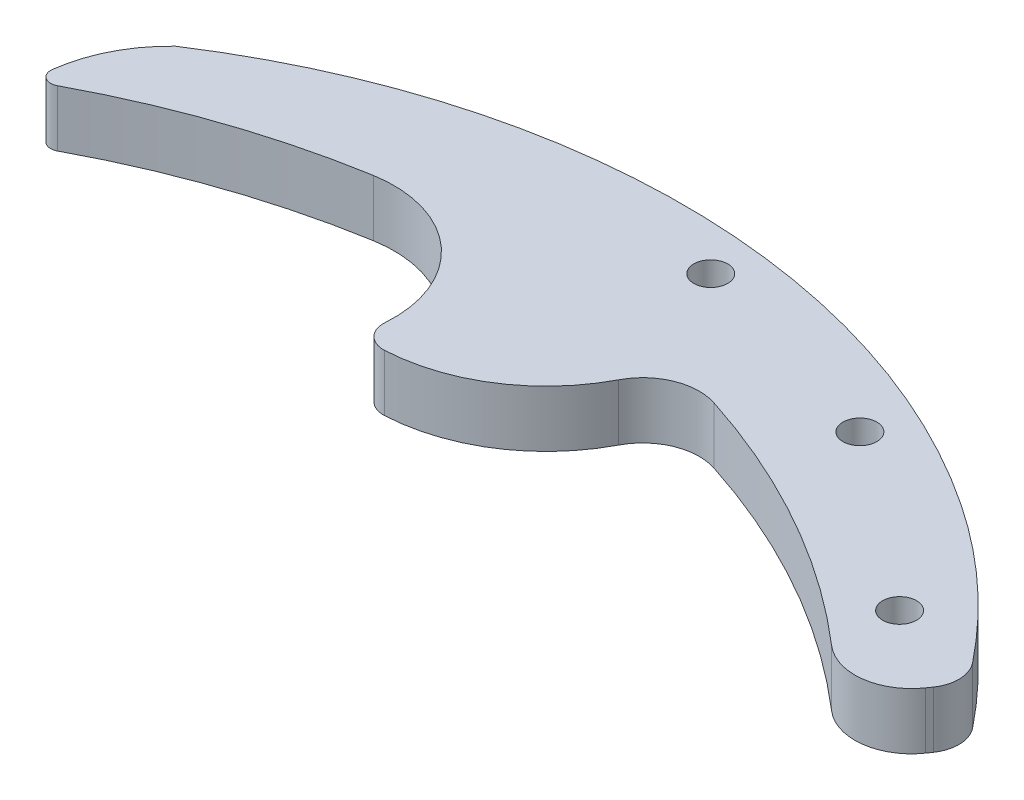
SolidWorks part; units mm, degrees
ref_plane "前视基准面" through (0, 0, 0) normal (0, 0, 1) x (1, 0, 0)
ref_plane "上视基准面" through (0, 0, 0) normal (0, 1, 0) x (1, 0, 0)
ref_plane "右视基准面" through (0, 0, 0) normal (1, 0, 0) x (0, 0, -1)
sketch "草图1" plane through (0, 0, 0) normal (0, 1, 0) x (1, 0, 0)
  line L0 (1.5548, -8.3375) -> (-0.4302, -6.7213)
  line L1 (8.1432, -4.501) -> (5.9156, -7.7187)
  circle A0 centre (-81.4137, 0.5413) radius 1.5
  circle A1 centre (0.783, -0.1362) radius 1.5
  circle A2 centre (-33.3548, 17.3022) radius 1.5
  arc A3 (1.5548, -8.3375) -> (5.9156, -7.7187) centre (3.449, -6.0111) ccw
  arc A4 (8.0213, -0.9218) -> (-4.5749, 10.6629) centre (-35.7028, -35.823) ccw
  arc A5 (8.1432, -4.501) -> (8.0213, -0.9218) centre (5.6767, -2.7934) ccw
  spline S0 degree 3 poles (-12.167, 2.5825) (-11.4471, 1.9213) (-10.023, 2.8082) (-8.9764, 1.8091) (-8.2135, 1.404) (-8.2004, 0.3499) (-8.0426, -0.494) (-7.819, -1.4294) (-6.8169, -1.7535) (-5.8636, -1.3425) (-4.7413, -1.711) (-4.0828, -2.6214) (-3.7925, -3.7512) (-3.9105, -4.8693) (-3.2321, -5.6268) (-2.2067, -6.0304) (-1.0461, -6.0626) (-0.5549, -6.5645) (-0.4302, -6.7213) knots 0 0 0 0 0.036098 0.047993 0.058182 0.069735 0.087709 0.096698 0.107024 0.126401 0.138603 0.153227 0.171393 0.187122 0.197486 0.211172 0.233173 0.241578 0.241578 0.241578 0.241578
  spline S1 degree 3 poles (-23.9106, 9.6057) (-23.5583, 9.383) (-22.85, 7.3001) (-21.4691, 8.0266) (-20.5876, 8.1152) (-19.7095, 8.3931) (-18.8874, 8.017) (-18.2164, 7.2706) (-17.5409, 6.4954) (-16.9173, 5.1698) (-15.3663, 5.5887) (-13.9067, 5.7479) (-12.701, 4.3501) (-12.8698, 3.1094) (-12.167, 2.5825) knots 0 0 0 0 0.161236 0.212348 0.265446 0.336193 0.378688 0.430637 0.526782 0.58317 0.682557 0.781271 0.853714 1 1 1 1
  spline S2 degree 3 poles (-47.715, 10.6051) (-47.069, 9.9007) (-45.1392, 9.958) (-43.922, 11.5864) (-42.4007, 11.771) (-41.3375, 11.3077) (-40.4081, 10.5714) (-39.2433, 10.6059) (-38.4214, 11.3898) (-37.3041, 11.739) (-35.96, 12.1777) (-35.1697, 11.0959) (-34.3091, 10.5976) (-33.2302, 10.3268) (-32.4836, 11.1725) (-31.5559, 11.5569) (-30.4962, 11.8332) (-29.5446, 11.0114) (-28.7649, 9.931) (-27.275, 9.7916) (-25.6779, 9.9955) (-24.4296, 10.4937) (-23.9106, 9.6057) knots 0 0 0 0 0.101433 0.182304 0.213922 0.268057 0.309966 0.345938 0.38914 0.432999 0.482664 0.529097 0.56672 0.598853 0.644173 0.680167 0.715861 0.759457 0.810996 0.863338 0.916048 1 1 1 1
  spline S3 degree 3 poles (-81.5422, -6.3513) (-81.0448, -4.2136) (-76.4233, -7.0442) (-77.1939, -1.4346) (-74.4996, -1.0071) (-72.1196, -0.982) (-72.0139, 2.5319) (-69.1934, 2.2708) (-66.979, 2.5768) (-66.7933, 4.5615) (-65.2282, 5.8665) (-63.7043, 5.4312) (-62.4807, 5.2334) (-61.4837, 6.1991) (-61.3006, 7.5032) (-59.7831, 8.3976) (-58.5198, 7.7031) (-57.096, 7.6588) (-55.836, 8.2946) (-55.3246, 9.9013) (-53.5853, 9.7021) (-52.4002, 9.4229) (-50.5844, 8.8131) (-50.168, 11.1139) (-48.3352, 11.1661) (-47.715, 10.6051) knots 0 0 0 0 0.100332 0.18604 0.234954 0.2703 0.337742 0.40192 0.43828 0.47683 0.523229 0.559517 0.584173 0.604077 0.648703 0.670042 0.71595 0.738313 0.768611 0.808998 0.834826 0.875875 0.9064 0.941714 1 1 1 1
  spline S4 degree 3 poles (-4.5749, 10.6629) (-7.0478, 12.3188) (-11.4724, 14.6182) (-18.6446, 18.4463) (-25.5528, 20.2853) (-32.3111, 21.7651) (-38.4562, 22.3345) (-46.0367, 22.338) (-53.5806, 21.3214) (-60.3919, 19.2596) (-67.9165, 16.4006) (-77.0441, 11.4902) (-84.2299, 5.0961) (-88.4718, 0.1048) (-88.5463, -3.0993) (-86.896, -6.5347) (-83.4963, -7.4095) (-81.5422, -6.3513) knots 0.083499 0.083499 0.083499 0.083499 0.162309 0.214041 0.297346 0.349154 0.396315 0.45953 0.548645 0.595484 0.646703 0.76082 0.864659 0.902713 0.926128 0.944547 1 1 1 1
extrude "凸台-拉伸1" add sketch "草图1" along normal blind 1.2
sketch "草图2" plane through (0, 1.2, 0) normal (0, 1, 0) x (1, 0, 0)
  line L0 (8.1432, -4.501) -> (5.9156, -7.7187)
  arc A0 (-4.5749, 10.6629) -> (8.0213, -0.9218) centre (-35.7028, -35.823) cw
  arc A1 (8.0213, -0.9218) -> (8.1432, -4.501) centre (5.6767, -2.7934) cw
  arc A2 (5.9156, -7.7187) -> (1.5548, -8.3375) centre (3.449, -6.0111) cw
  arc A3 (1.5548, -8.3375) -> (-81.5422, -6.3513) centre (-41.2747, -60.9404) ccw
  arc A4 (-4.5749, 10.6629) -> (-88.4233, -1.3571) centre (-39.8161, -41.9658) ccw
  arc A5 (-88.4233, -1.3571) -> (-81.5422, -6.3513) centre (-84.1899, -2.7618) ccw
  spline S1 degree 3 poles (-4.5749, 10.6629) (-7.0478, 12.3188) (-11.4724, 14.6182) (-18.6446, 18.4463) (-25.5528, 20.2853) (-32.3111, 21.7651) (-38.4562, 22.3345) (-46.0367, 22.338) (-53.5806, 21.3214) (-60.3919, 19.2596) (-67.9165, 16.4006) (-77.0441, 11.4902) (-84.2299, 5.0961) (-88.4718, 0.1048) (-88.5463, -3.0993) (-86.896, -6.5347) (-83.4963, -7.4095) (-81.5422, -6.3513) knots 0.083499 0.083499 0.083499 0.083499 0.162309 0.214041 0.297346 0.349154 0.396315 0.45953 0.548645 0.595484 0.646703 0.76082 0.864659 0.902713 0.926128 0.944547 1 1 1 1 construction
extrude "凸台-拉伸2" add sketch "草图2" along normal blind 10
sketch "草图3" plane through (0, 11.2, 0) normal (0, 1, 0) x (1, 0, 0)
  line L1 (-87.507, -5.7437) -> (-106.1413, 14.9858)
  line L2 (-106.1413, 14.9858) -> (-8.2419, 31.2068)
  line L3 (-8.2419, 31.2068) -> (8.9622, 13.4293)
  line L4 (8.9622, 13.4293) -> (8.0213, -0.9218)
  line L5 (1.5548, -8.3375) -> (-81.5422, -6.3513)
  arc A0 (-88.4233, -1.3571) -> (-4.5749, 10.6629) centre (-39.8161, -41.9658) cw
  arc A1 (-4.5749, 10.6629) -> (2.1688, 5.355) centre (-35.7028, -35.823) cw
  arc A2 (8.0213, -0.9218) -> (-4.5749, 10.6629) centre (-35.7028, -35.823) ccw construction
  arc A3 (2.1688, 5.355) -> (8.0213, -0.9218) centre (-35.7028, -35.823) cw
  arc A6 (1.5548, -8.3375) -> (-81.5422, -6.3513) centre (-41.2747, -60.9404) ccw
  arc A7 (-88.4233, -1.3571) -> (-87.507, -5.7437) centre (-84.1899, -2.7618) ccw
extrude "切除-拉伸1" cut sketch "草图3" against normal through all both and the other way through all
sketch "草图4" plane through (0, 0, 0) normal (0, -1, 0) x (1, 0, 0)
  circle A0 centre (0.783, 0.1362) radius 1.5
extrude "切除-拉伸2" cut sketch "草图4" against normal blind 5000
sketch "草图5" plane through (0, 0, 0) normal (0, -1, 0) x (-1, 0, 0)
  circle A0 centre (33.3548, 17.3022) radius 1.5
  circle A1 centre (81.4137, 0.5413) radius 1.5
extrude "切除-拉伸3" cut sketch "草图5" against normal blind 500
sketch "草图9" plane through (0, 0, 0) normal (0, -1, 0) x (1, 0, 0)
  arc A0 (-33.3548, -17.3022) -> (0.783, 0.1362) centre (-38.7124, 35.3197) ccw construction
  arc A3 (-4.5749, -10.6629) -> (8.0213, 0.9218) centre (-35.7028, 35.823) ccw construction
  circle A4 centre (-14.6505, -11.7844) radius 1.5
  dimension "D1" = 3
extrude "切除-拉伸6" cut sketch "草图9" against normal blind 500
sketch "草图6" plane through (0, 0, 0) normal (0, -1, 0) x (1, 0, 0)
  line L1 (-111.3678, 10.4513) -> (22.6991, 10.4513)
  line L2 (-111.3678, 10.4513) -> (-111.3678, -37.8774)
  line L3 (-111.3678, -37.8774) -> (22.6991, -37.8774)
  line L4 (22.6991, 10.4513) -> (22.6991, -37.8774)
  line L5 (-111.3678, 10.4513) -> (22.6991, -37.8774) construction
  line L6 (-111.3678, -37.8774) -> (22.6991, 10.4513) construction
  point P0 (-44.3344, -13.7131)
extrude "切除-拉伸4" cut sketch "草图6" against normal up to surface (1.2 mm away)
sketch "草图7" plane through (0, 1.2, 0) normal (0, -1, 0) x (1, 0, 0)
  line L1 (-115.2098, 16.5177) -> (21.0814, 16.5177)
  line L2 (-115.2098, 16.5177) -> (-115.2098, -38.0797)
  line L3 (-115.2098, -38.0797) -> (21.0814, -38.0797)
  line L4 (21.0814, 16.5177) -> (21.0814, -38.0797)
  line L5 (-115.2098, 16.5177) -> (21.0814, -38.0797) construction
  line L6 (-115.2098, -38.0797) -> (21.0814, 16.5177) construction
  point P0 (-47.0642, -10.781)
extrude "切除-拉伸5" cut sketch "草图7" against normal blind 5
sketch "草图8" plane through (0, 11.2, 0) normal (0, 1, 0) x (1, 0, 0)
  circle A0 centre (-81.4137, 0.5413) radius 2.505
extrude "凸台-拉伸3" add sketch "草图8" against normal up to surface (5 mm away)
sketch "草图12" plane through (0, 11.2, 0) normal (0, 1, 0) x (1, 0, 0)
  line L0 (-58.6398, 18.5106) -> (-112.0714, 17.291)
  line L1 (-112.0714, 17.291) -> (-102.0356, -15.6835)
  line L2 (-102.0356, -15.6835) -> (-71.1093, -17.7999)
  line L3 (-71.1093, -17.7999) -> (-72.5834, -0.7639)
  arc A0 (-87.4966, -0.273) -> (-86.8788, -6.3205) centre (-84.3771, -3.0096) ccw
  arc A1 (-4.5749, 10.6629) -> (-88.4233, -1.3571) centre (-39.8161, -41.9658) ccw construction
  arc A2 (-88.4233, -1.3571) -> (-81.5422, -6.3513) centre (-84.1899, -2.7618) ccw construction
  arc A3 (-58.6398, 18.5106) -> (-87.4966, -0.273) centre (-39.6096, -42.2831) ccw
  arc A4 (-86.8788, -6.3205) -> (-81.5422, -6.3513) centre (-84.1899, -2.7618) ccw
  arc A5 (-81.5422, -6.3513) -> (-72.5834, -0.7639) centre (-41.2747, -60.9404) cw
  arc A6 (1.5548, -8.3375) -> (-81.5422, -6.3513) centre (-41.2747, -60.9404) ccw construction
extrude "切除-拉伸7" cut sketch "草图12" against normal blind 500
sketch "草图13" plane through (0, 11.2, 0) normal (0, 1, 0) x (1, 0, 0)
  line L0 (-58.6398, 18.5106) -> (-93.7159, 19.5163)
  line L1 (-93.7159, 19.5163) -> (-99.0262, -9.0263)
  line L2 (-99.0262, -9.0263) -> (-86.0751, -21.4722)
  line L3 (-86.0751, -21.4722) -> (-50.7361, -15.2492)
  line L4 (-50.7361, -15.2492) -> (-34.7224, -9.0263)
  line L5 (-34.7224, -9.0263) -> (-40.736, 6.8914)
  arc A0 (-58.6398, 18.5106) -> (-87.3243, -0.0773) centre (-39.6097, -42.2829) ccw
  arc A1 (-87.3243, -0.0773) -> (-85.1888, -2.595) centre (-86.0751, -1.1823) ccw
  arc A3 (-85.1888, -2.595) -> (-40.736, 6.8914) centre (-49.9698, -58.7345) cw
  arc A4 (1.5548, -8.3375) -> (-81.5422, -6.3513) centre (-41.2747, -60.9404) ccw construction
extrude "切除-拉伸8" cut sketch "草图13" against normal blind 500
sketch "草图14" plane through (0, 11.2, 0) normal (0, 1, 0) x (1, 0, 0)
  line L1 (-85.1888, -2.595) -> (9.4103, -16.3352)
  line L2 (9.4103, -16.3352) -> (3.8705, -8.9813)
  arc A0 (-85.1888, -2.595) -> (3.8705, -8.9813) centre (-44.3816, -57.6991) cw
  arc A1 (1.5548, -8.3375) -> (5.9156, -7.7187) centre (3.449, -6.0111) ccw construction
extrude "切除-拉伸9" cut sketch "草图14" against normal blind 500
fillet "圆角2" radius 5 1 edges at (3.8705, 8.7, 8.9813)
sketch "草图16" plane through (0, 11.2, 0) normal (0, 1, 0) x (1, 0, 0)
  arc A1 (-55.7949, 9.9132) -> (-44.3816, -2.9107) centre (-54.1085, -0.0768) cw
  arc A2 (0.4799, -5.8423) -> (-85.1888, -2.595) centre (-44.3816, -57.6991) ccw construction
  arc A3 (-55.7949, 9.9132) -> (-27.9361, 8.8684) centre (-44.3816, -57.6991) cw
  arc A4 (-44.3816, -2.9107) -> (-27.9361, 8.8684) centre (-42.6824, 12.0868) ccw
  point P0 (-44.3816, -2.9107)
extrude "凸台-拉伸4" add sketch "草图16" against normal up to surface (5 mm away)
fillet "圆角3" radius 5 1 edges at (-27.9361, 8.7, -8.8684)
fillet "圆角4" radius 2 1 edges at (-44.3816, 8.7, 2.9107)
sketch "草图17" plane through (0, 11.2, 0) normal (0, 1, 0) x (1, 0, 0)
  line L0 (-78.1888, 1.9562) -> (-81.1297, -16.6738)
  line L1 (-81.1297, -16.6738) -> (-94.7098, -4.5882)
  line L2 (-94.7098, -4.5882) -> (-97.1789, 7.1726)
  line L3 (-97.1789, 7.1726) -> (-87.3243, -0.0773)
  arc A0 (-72.2454, 12.7068) -> (-78.1888, 1.9562) centre (-66.1332, 2.3096) ccw
  arc A2 (-55.7949, 9.9132) -> (-85.1888, -2.595) centre (-44.3816, -57.6991) ccw construction
  arc A3 (-87.3243, -0.0773) -> (-72.2454, 12.7068) centre (-42.9399, -37.1439) cw
  dimension "D1" = 7
extrude "切除-拉伸10" cut sketch "草图17" against normal blind 50
fillet "圆角5" radius 1 1 edges at (-78.1888, 8.7, -1.9562)
